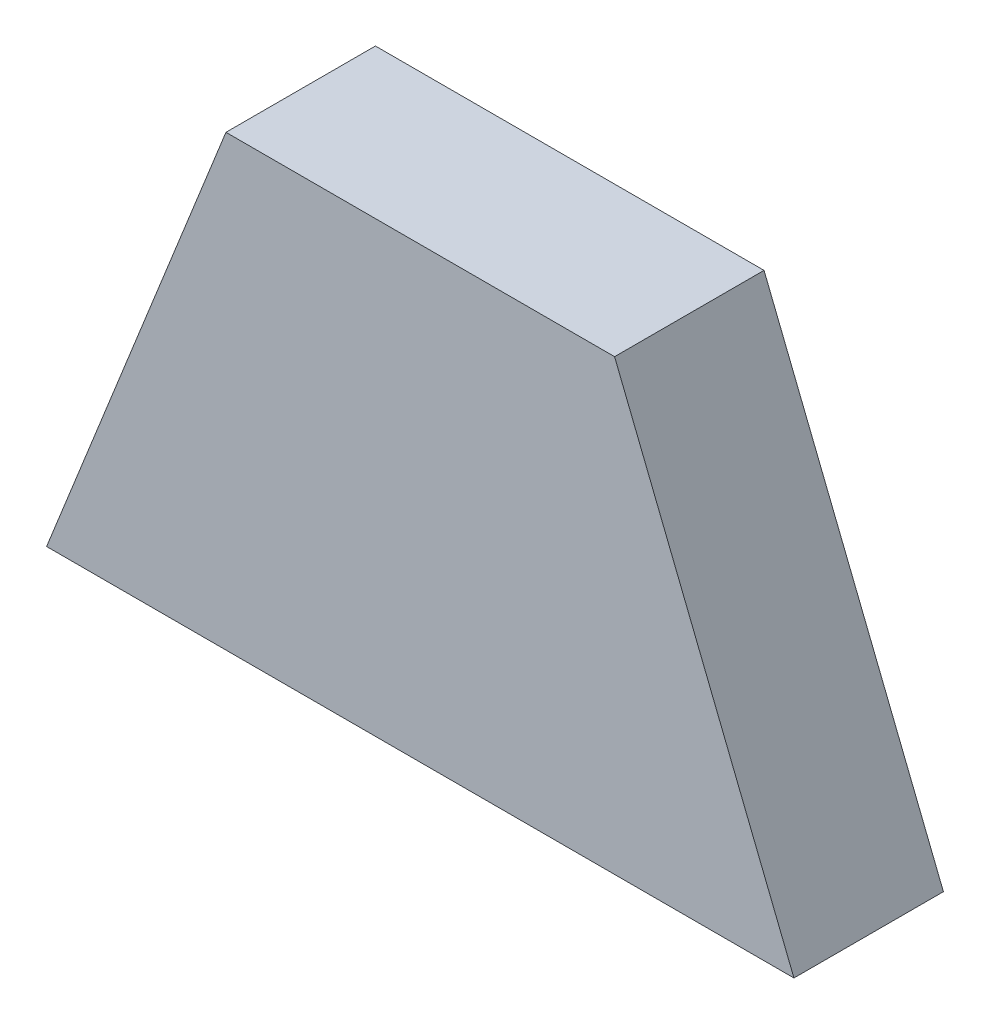
SolidWorks part; units mm, degrees
ref_plane "前基準面" through (0, 0, 0) normal (0, 0, 1) x (1, 0, 0)
ref_plane "上基準面" through (0, 0, 0) normal (0, 1, 0) x (1, 0, 0)
ref_plane "右基準面" through (0, 0, 0) normal (1, 0, 0) x (0, 0, -1)
sketch "草圖1" plane through (0, 0, 0) normal (0, 0, 1) x (1, 0, 0)
  line L0 (0, 0) -> (50, 0)
  line L1 (27.5, 0) -> (-27.5, 0) construction
  line L2 (50, 0) -> (38, 30)
  line L3 (38, 30) -> (12, 30)
  line L4 (12, 30) -> (0, 0)
  dimension "D1" = 26
  dimension "D2" = 30
  dimension "D3" = 12
  dimension "D4" = 12
  dimension "D5" = 50
extrude "填料-伸長1" add sketch "草圖1" against normal blind 10
